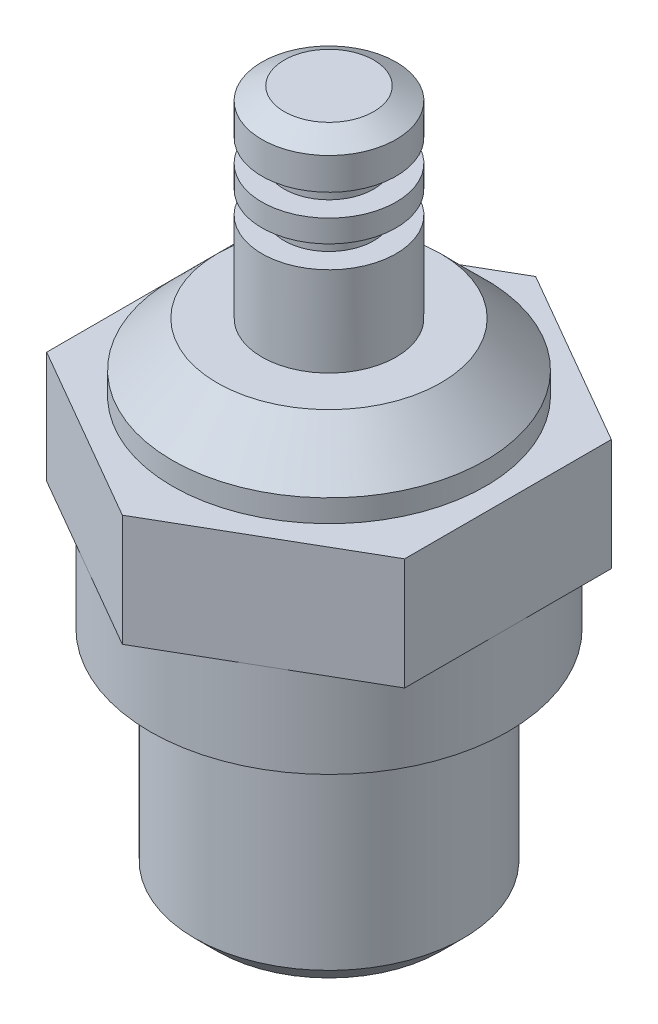
SolidWorks part; units mm, degrees
material "Plain Carbon Steel"
ref_plane "Front Plane" through (0, 0, 0) normal (0, 0, 1) x (1, 0, 0)
ref_plane "Top Plane" through (0, 0, 0) normal (0, 1, 0) x (1, 0, 0)
ref_plane "Right Plane" through (0, 0, 0) normal (1, 0, 0) x (0, 0, -1)
sketch "Sketch5" plane through (0, 0, 0) normal (0, 1, 0) x (1, 0, 0)
  line L1 (-4, 2.3094) -> (-4, -2.3094)
  line L2 (-4, -2.3094) -> (0, -4.6188)
  line L3 (0, -4.6188) -> (4, -2.3094)
  line L4 (4, -2.3094) -> (4, 2.3094)
  line L5 (4, 2.3094) -> (0, 4.6188)
  line L6 (0, 4.6188) -> (-4, 2.3094)
  circle A0 centre (0, 0) radius 4 construction
  dimension "D1" = 8
extrude "Boss-Extrude5" add sketch "Sketch5" along normal blind 2.5
sketch "Sketch6" plane through (0, 0, 0) normal (0, -1, 0) x (1, 0, 0)
  circle A0 centre (0, 0) radius 4
extrude "Boss-Extrude6" add sketch "Sketch6" along normal blind 2
sketch "Sketch7" plane through (0, -2, 0) normal (0, -1, 0) x (1, 0, 0)
  circle A0 centre (0, 0) radius 3
  circle A1 centre (0, 0) radius 4 construction
  dimension "D1" = 1
extrude "Boss-Extrude7" add sketch "Sketch7" along normal blind 5
sketch "Sketch8" plane through (0, -7, 0) normal (0, -1, 0) x (1, 0, 0)
  circle A0 centre (0, 0) radius 1.5
  dimension "D1" = 3
extrude "Cut-Extrude1" cut sketch "Sketch8" against normal blind 4
sketch "Sketch9" plane through (0, 2.5, 0) normal (0, 1, 0) x (1, 0, 0)
  circle A0 centre (0, 0) radius 1.5
  dimension "D1" = 3
extrude "Boss-Extrude8" add sketch "Sketch9" along normal blind 3.5
sketch "Sketch10" plane through (0, 2.5, 0) normal (0, 1, 0) x (1, 0, 0)
  circle A0 centre (0, 0) radius 3.5
  dimension "D1" = 7
extrude "Boss-Extrude9" add sketch "Sketch10" along normal blind 0.5
sketch "Sketch11" plane through (0, 3, 0) normal (0, 1, 0) x (1, 0, 0)
  circle A0 centre (0, 0) radius 3.5
  dimension "D1" = 7
extrude "Boss-Extrude10" add sketch "Sketch11" along normal blind 1 draft 45
sketch "Sketch12" plane through (0, -7, 0) normal (0, -1, 0) x (1, 0, 0)
  circle A0 centre (0, 0) radius 1.5
  dimension "D1" = 3
extrude "Boss-Extrude11" add sketch "Sketch12" against normal blind 11.5 from offset 4 offset against normal yes
sketch "Sketch13" plane through (0, -7, 0) normal (0, -1, 0) x (1, 0, 0)
  circle A0 centre (0, 0) radius 1.5
  circle A1 centre (0, 0) radius 1
  dimension "D1" = 3
  dimension "D2" = 2
extrude "Cut-Extrude2" cut sketch "Sketch13" against normal blind 0.5 from offset 13 offset against normal yes
sketch "Sketch14" plane through (0, 6.5, 0) normal (0, -1, 0) x (1, 0, 0)
  circle A0 centre (0, 0) radius 1 construction
  circle A1 centre (0, 0) radius 1.5
  circle A2 centre (0, 0) radius 1.5
  circle A3 centre (0, 0) radius 1
  dimension "D1" = 0
extrude "Cut-Extrude3" cut sketch "Sketch14" against normal blind 0.5 from offset 0.5 offset against normal yes
chamfer "Chamfer1" distance 0.5 angle 30 1 edges at (0, 8.5, -1.5)
chamfer "Chamfer2" distance 0.5 angle 45 1 edges at (0, -7, -3)
